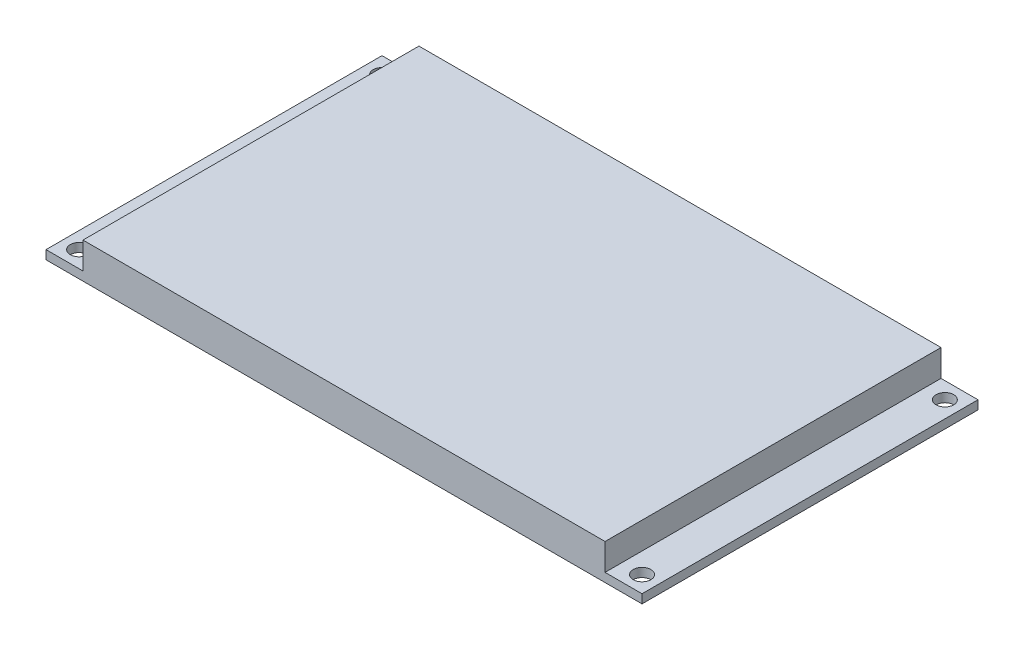
SolidWorks part; units mm, degrees
ref_plane "前视基准面" through (0, 0, 0) normal (0, 0, 1) x (1, 0, 0)
ref_plane "上视基准面" through (0, 0, 0) normal (0, 1, 0) x (1, 0, 0)
ref_plane "右视基准面" through (0, 0, 0) normal (1, 0, 0) x (0, 0, -1)
sketch "草图1" plane through (0, 0, 0) normal (0, 1, 0) x (1, 0, 0)
  line L0 (54, 60.88) -> (54, 0) construction
  line L1 (0, 0) -> (108, 0)
  line L2 (0, 0) -> (0, 60.88)
  line L3 (0, 60.88) -> (108, 60.88)
  line L4 (108, 0) -> (108, 60.88)
  circle A0 centre (3, 57.88) radius 1.6
  circle A1 centre (3, 3) radius 1.6
  circle A2 centre (105, 3) radius 1.6
  circle A3 centre (105, 57.88) radius 1.6
  dimension "D3" = 3.2
  dimension "D4" = 3.2
  dimension "D1" = 108
  dimension "D2" = 60.88
  dimension "D5" = 3
  dimension "D6" = 3
  dimension "D7" = 3
  dimension "D8" = 3
extrude "凸台-拉伸1" add sketch "草图1" along normal blind 1.6
sketch "草图2" plane through (0, 1.6, 0) normal (0, 1, 0) x (1, 0, 0)
  line L0 (108, 60.88) -> (0, 60.88) construction
  line L1 (6.7, 60.88) -> (101.3, 60.88)
  line L2 (6.7, 60.88) -> (6.7, 0)
  line L3 (6.7, 0) -> (101.3, 0)
  line L4 (101.3, 60.88) -> (101.3, 0)
  line L5 (0, 0) -> (108, 0) construction
  line L6 (0, 60.88) -> (0, 0) construction
  dimension "D1" = 94.6
  dimension "D2" = 6.7
extrude "凸台-拉伸2" add sketch "草图2" along normal blind 4.85
sketch "草图3" plane through (0, 0, 0) normal (0, -1, 0) x (1, 0, 0)
  line L0 (0, -60.88) -> (0, 0) construction
  line L1 (0, -12.66) -> (3, -12.66)
  line L2 (0, -12.66) -> (0, -48.22)
  line L3 (0, -48.22) -> (3, -48.22)
  line L4 (3, -12.66) -> (3, -48.22)
  line L5 (108, -60.88) -> (0, -60.88) construction
  dimension "D1" = 35.56
  dimension "D2" = 12.66
  dimension "D3" = 3
extrude "凸台-拉伸3" add sketch "草图3" along normal blind 8.34
